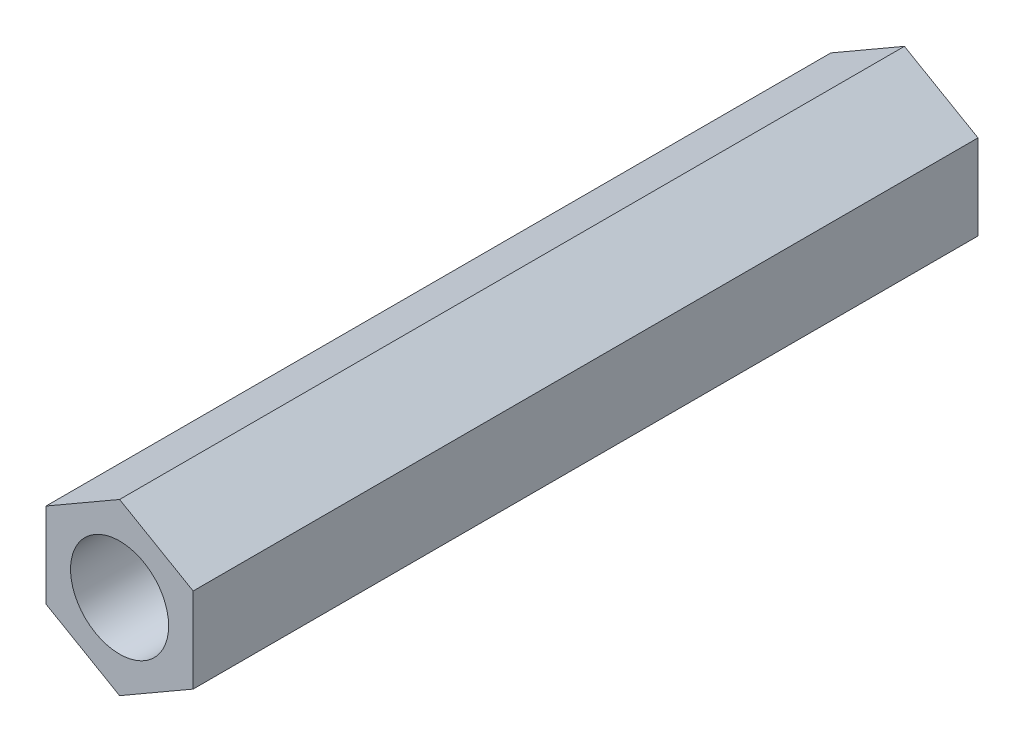
SolidWorks part; units mm, degrees
ref_plane "前视基准面" through (0, 0, 0) normal (0, 0, 1) x (1, 0, 0)
ref_plane "上视基准面" through (0, 0, 0) normal (0, 1, 0) x (1, 0, 0)
ref_plane "右视基准面" through (0, 0, 0) normal (1, 0, 0) x (0, 0, -1)
sketch "草图1" plane through (0, 0, 0) normal (0, 0, 1) x (1, 0, 0)
  line L1 (1.5, 0.866) -> (0, 1.7321)
  line L2 (0, 1.7321) -> (-1.5, 0.866)
  line L3 (-1.5, 0.866) -> (-1.5, -0.866)
  line L4 (-1.5, -0.866) -> (0, -1.7321)
  line L5 (0, -1.7321) -> (1.5, -0.866)
  line L6 (1.5, -0.866) -> (1.5, 0.866)
  circle A0 centre (0, 0) radius 1
  circle A1 centre (0, 0) radius 1.5 construction
  dimension "D1" = 2
  dimension "D2" = 3
extrude "凸台-拉伸1" add sketch "草图1" along normal blind 16
